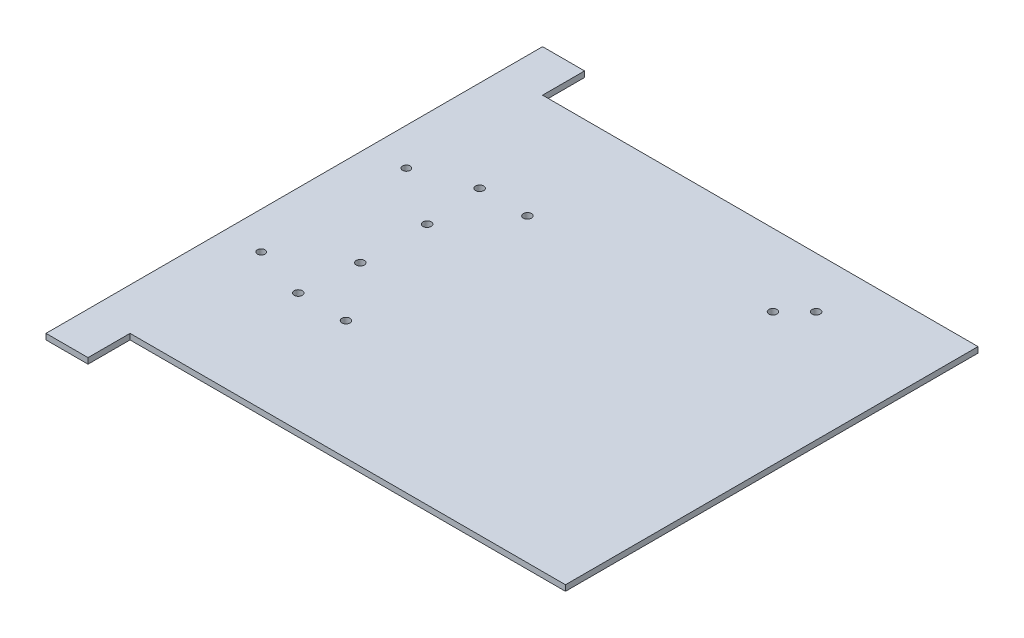
SolidWorks part; units mm, degrees
ref_plane "Front Plane" through (0, 0, 0) normal (0, 0, 1) x (1, 0, 0)
ref_plane "Top Plane" through (0, 0, 0) normal (0, 1, 0) x (1, 0, 0)
ref_plane "Right Plane" through (0, 0, 0) normal (1, 0, 0) x (0, 0, -1)
sketch "Sketch1" plane through (0, 0, 0) normal (0, 1, 0) x (1, 0, 0)
  line L0 (-360, -130) -> (-360, 130)
  line L1 (-360, 130) -> (-338, 130)
  line L2 (-338, 130) -> (-338, 108)
  line L3 (-338, 108) -> (338, 108)
  line L4 (0, 0) -> (0, 314.8416) construction
  line L5 (0, 0) -> (-620.0064, 0) construction
  line L6 (-338, -108) -> (338, -108)
  line L7 (-338, -130) -> (-338, -108)
  line L8 (-360, -130) -> (-338, -130)
  line L9 (360, -130) -> (338, -130)
  line L10 (338, -130) -> (338, -108)
  line L11 (338, 130) -> (338, 108)
  line L12 (360, 130) -> (338, 130)
  line L13 (360, -130) -> (360, 130)
  point P13 (-360, 0)
  point P16 (0, -108)
  point P17 (0, 108)
  point P19 (360, 0)
  dimension "D1" = 22
  dimension "D2" = 130
  dimension "D3" = 22
  dimension "D4" = 360
extrude "Boss-Extrude1" add sketch "Sketch1" along normal blind 3
sketch "Sketch2" plane through (0, 3, 0) normal (0, 1, 0) x (1, 0, 0)
  circle A0 centre (307.7639, 49.3029) radius 2.125
  circle A1 centre (282.7639, 49.3029) radius 2.125
  circle A2 centre (305.2639, 19.3029) radius 2.125
  circle A3 centre (305.2639, -15.6971) radius 2.125
  circle A4 centre (307.7639, -45.6971) radius 2.125
  circle A5 centre (282.7639, -45.6971) radius 2.125
  circle A6 centre (-287.2361, -45.6971) radius 2.125
  circle A7 centre (-312.2361, -45.6971) radius 2.125
  circle A8 centre (-309.7361, -15.6971) radius 2.125
  circle A9 centre (-309.7361, 19.3029) radius 2.125
  circle A10 centre (-287.2361, 49.3029) radius 2.125
  circle A11 centre (-312.2361, 49.3029) radius 2.125
extrude "Cut-Extrude1" cut sketch "Sketch2" against normal blind 3
sketch "Sketch3" plane through (0, 3, 0) normal (0, 1, 0) x (1, 0, 0)
  circle A0 centre (339.441, 39.2438) radius 2
  circle A1 centre (339.441, -36.7562) radius 2
  circle A2 centre (-340.559, -36.7562) radius 2
  circle A3 centre (-340.559, 39.2438) radius 2
extrude "Cut-Extrude2" cut sketch "Sketch3" against normal blind 3
sketch "Sketch4" plane through (0, 3, 0) normal (0, 1, 0) x (1, 0, 0)
  line L0 (-213.5102, 126.7637) -> (123.2837, -210.0302) construction
  circle A0 centre (66.6096, -175.9836) radius 2.125
  circle A1 centre (-179.4635, 70.0896) radius 2.125
  circle A2 centre (-15.4148, -93.9592) radius 2.125
  circle A3 centre (-97.4391, -11.9348) radius 2.125
  circle A4 centre (77.9233, -164.6698) radius 2.125
  circle A5 centre (-4.101, -82.6455) radius 2.125
  circle A6 centre (-86.1254, -0.6211) radius 2.125
  circle A7 centre (-168.1498, 81.4033) radius 2.125
  circle A8 centre (-49.3559, 200.1973) radius 2.125
  circle A9 centre (32.6685, 118.1729) radius 2.125
  circle A10 centre (114.6929, 36.1485) radius 2.125
  circle A11 centre (196.7173, -45.8759) radius 2.125
  circle A12 centre (43.9822, 129.4866) radius 2.125
  circle A13 centre (126.0066, 47.4622) radius 2.125
  circle A14 centre (-38.0422, 211.511) radius 2.125
  circle A15 centre (208.031, -34.5622) radius 2.125
  point P10 (-56.4269, -52.947)
  point P35 (84.9944, 88.4744)
  dimension "D1" = 4.25
  dimension "D2" = 4.25
  dimension "D4" = 4.25
  dimension "D6" = 4.25
  dimension "D3" = 348
  dimension "D5" = 116
  dimension "D7" = 116
extrude "Cut-Extrude3" cut sketch "Sketch4" against normal blind 3
sketch "Sketch5" plane through (0, 3, 0) normal (0, 1, 0) x (1, 0, 0)
  line L1 (360, -130) -> (-110, -130)
  line L2 (360, -130) -> (360, 130)
  line L3 (360, 130) -> (-110, 130)
  line L4 (-110, -130) -> (-110, 130)
  line L5 (-360, 130) -> (-360, -130) construction
  line L6 (360, 130) -> (338, 130) construction
  dimension "D1" = 250
  dimension "D2" = 0
extrude "Cut-Extrude4" cut sketch "Sketch5" against normal blind 3
